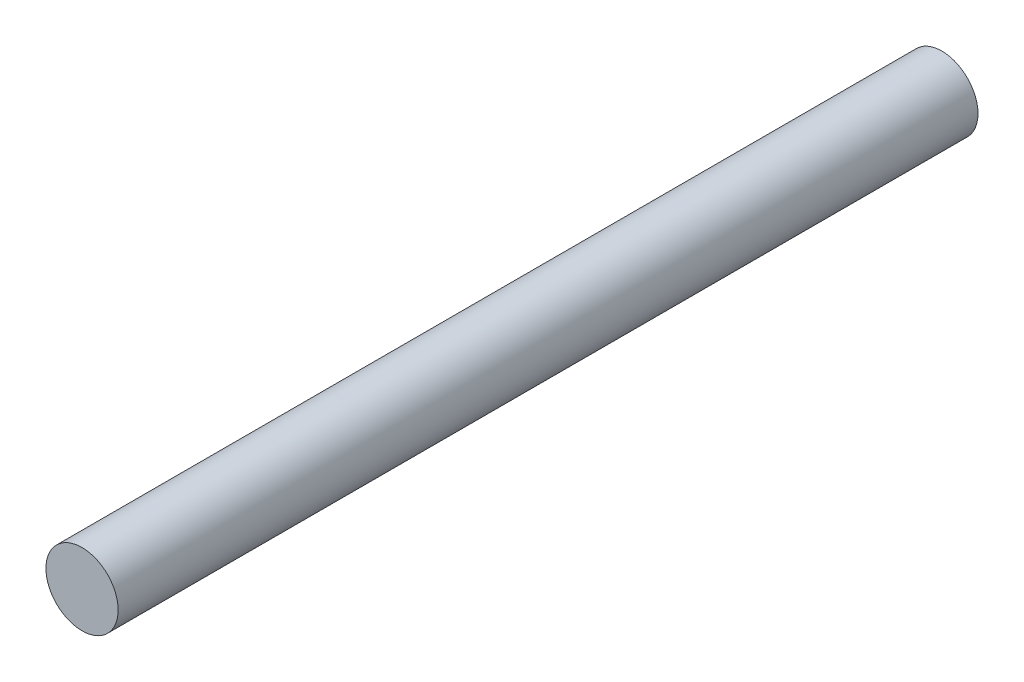
SolidWorks part; units mm, degrees
ref_plane "Front Plane" through (0, 0, 0) normal (0, 0, 1) x (1, 0, 0)
ref_plane "Top Plane" through (0, 0, 0) normal (0, 1, 0) x (1, 0, 0)
ref_plane "Right Plane" through (0, 0, 0) normal (1, 0, 0) x (0, 0, -1)
sketch "Sketch2" plane through (0, 0, 0) normal (0, 0, 1) x (1, 0, 0)
  circle A0 centre (0, 0) radius 6.2
  dimension "D1" = 12.4
extrude "Boss-Extrude1" add sketch "Sketch2" along normal blind 147.7
